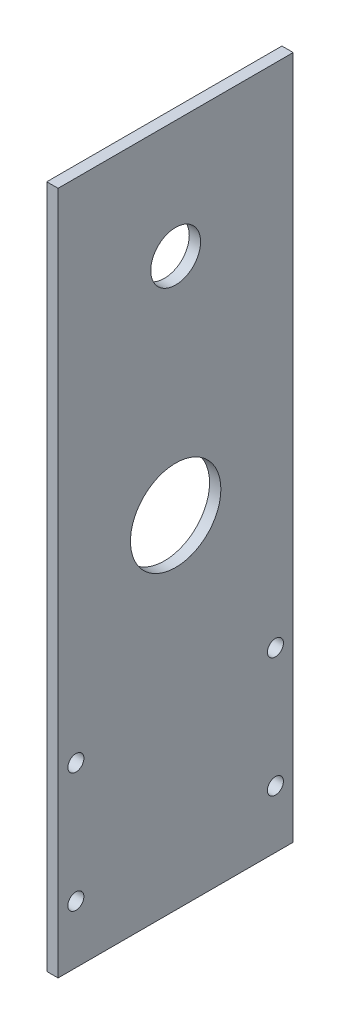
SolidWorks part; units mm, degrees
ref_plane "Front Plane" through (0, 0, 0) normal (1, 0, 0) x (0, 1, 0)
ref_plane "Top Plane" through (0, 0, 0) normal (0, 0, 1) x (0, 1, 0)
ref_plane "Right Plane" through (0, 0, 0) normal (0, 1, 0) x (-1, 0, 0)
sketch "Sketch1" plane through (0, 0, 0) normal (1, 0, 0) x (0, 1, 0)
  line L0 (-46.2079, -28.02) -> (-79.8319, -28.02) construction
  line L1 (96.0399, -33.02) -> (-96.0399, -33.02)
  line L2 (96.0399, -33.02) -> (96.0399, 33.02)
  line L3 (96.0399, 33.02) -> (-96.0399, 33.02)
  line L4 (-96.0399, -33.02) -> (-96.0399, 33.02)
  line L5 (96.0399, -33.02) -> (-96.0399, 33.02) construction
  line L6 (96.0399, 33.02) -> (-96.0399, -33.02) construction
  line L8 (-96.0399, 33.02) -> (-96.0399, -33.02)
  line L15 (-46.2079, -28.02) -> (-46.2079, 28.02) construction
  line L16 (-46.2079, 28.02) -> (-79.8319, 28.02) construction
  line L17 (-79.8319, -28.02) -> (-79.8319, 28.02) construction
  line L18 (-46.2079, -28.02) -> (-79.8319, 28.02) construction
  line L19 (-46.2079, 28.02) -> (-79.8319, -28.02) construction
  circle A0 centre (63.0199, 0) radius 7
  circle A1 centre (0, 0) radius 12.7
  circle A2 centre (-79.8319, 28.02) radius 2.25
  circle A3 centre (-79.8319, -28.02) radius 2.25
  circle A4 centre (-46.2079, -28.02) radius 2.25
  circle A5 centre (-46.2079, 28.02) radius 2.25
  point P0 (0, 0)
  point P6 (0, 0)
  point P9 (-70.1233, 0)
  point P10 (-71.4582, 33.02)
  point P11 (0, 0)
  point P19 (-63.0199, 0)
  point P24 (-63.0199, 33.02)
  point P27 (-40.524, -56.282)
  dimension "D4" = 14
  dimension "D5" = 25.4
  dimension "D9" = 4.5
  dimension "D1" = 159.0599
  dimension "D2" = 192.0799
  dimension "D3" = 66.04
  dimension "D6" = 126.0399
  dimension "D7" = 33.624
  dimension "D8" = 56.04
extrude "Boss-Extrude1" add sketch "Sketch1" along normal blind 3.175 contours L4 L1 L2 L3 A0
